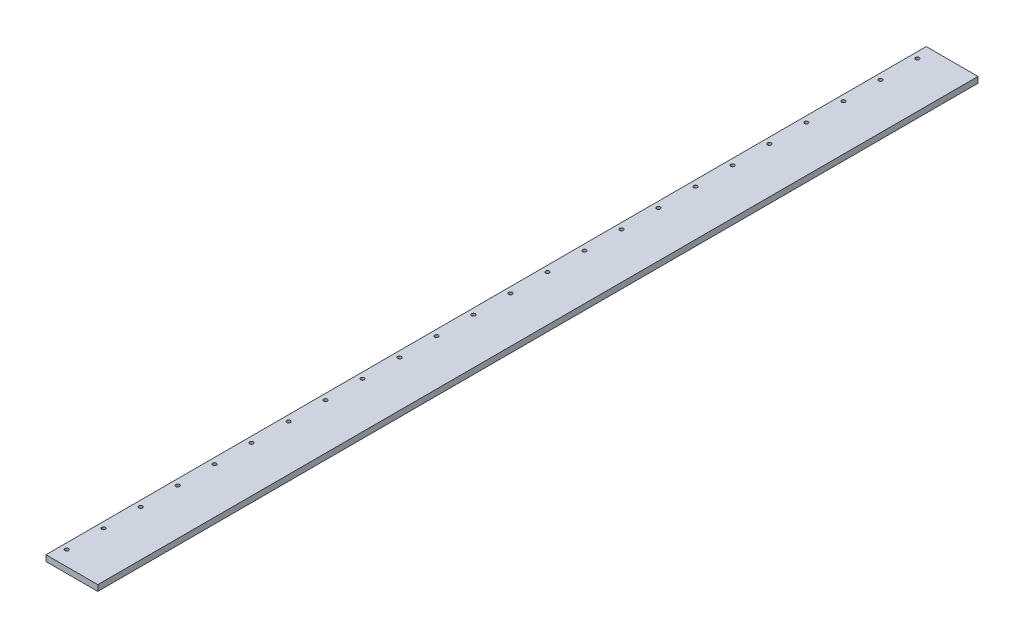
SolidWorks part; units mm, degrees
ref_plane "Front Plane" through (0, 0, 0) normal (0, 0, 1) x (1, 0, 0)
ref_plane "Top Plane" through (0, 0, 0) normal (0, 1, 0) x (1, 0, 0)
ref_plane "Right Plane" through (0, 0, 0) normal (1, 0, 0) x (0, 0, -1)
sketch "Sketch1" plane through (0, 0, 0) normal (0, 0, 1) x (1, 0, 0)
  line L1 (-16.5, -2) -> (18.5, -2)
  line L2 (-16.5, -2) -> (-16.5, 2)
  line L3 (-16.5, 2) -> (18.5, 2)
  line L4 (18.5, -2) -> (18.5, 2)
  line L5 (-16.5, -2) -> (18.5, 2) construction
  line L6 (-16.5, 2) -> (18.5, -2) construction
  point P0 (1, 0)
  dimension "D1" = 4
  dimension "D2" = 35
extrude "Boss-Extrude1" add sketch "Sketch1" along normal blind 595
sketch "Sketch2" plane through (0, 2, 0) normal (0, 1, 0) x (1, 0, 0)
  line L0 (-16.5, -595) -> (-16.5, 0) construction
  line L1 (18.5, 0) -> (-16.5, 0) construction
  point P0 (-12.5, -10)
  dimension "D1" = 4
  dimension "D2" = 10
hole_wizard "M3 Tapped Hole1" positions "3DSketch1" profile "Sketch3" tap size "M3" standard "DIN" end condition through all
sketch3d "3DSketch1"
  point P0 (-12.5, 2, 10)
sketch "Sketch3" plane through (-12.5, 2, 10) normal (1, 0, 0) x (0, 0, 1)
  line L0 (0, 0) -> (0, 4)
  line L1 (0, 4) -> (1.25, 4)
  line L2 (1.25, 4) -> (1.25, 0)
  line L5 (1.25, 0) -> (0, 0)
  line L11 (0, -6.35) -> (0, 107.95) construction
  dimension "Thread Major Dia." = 2.5
  dimension "Thru Tap Drill Depth" = 4
pattern_linear "LPattern1" count 24 spacing 25 along (0, 0, 1) of "M3 Tapped Hole1"
